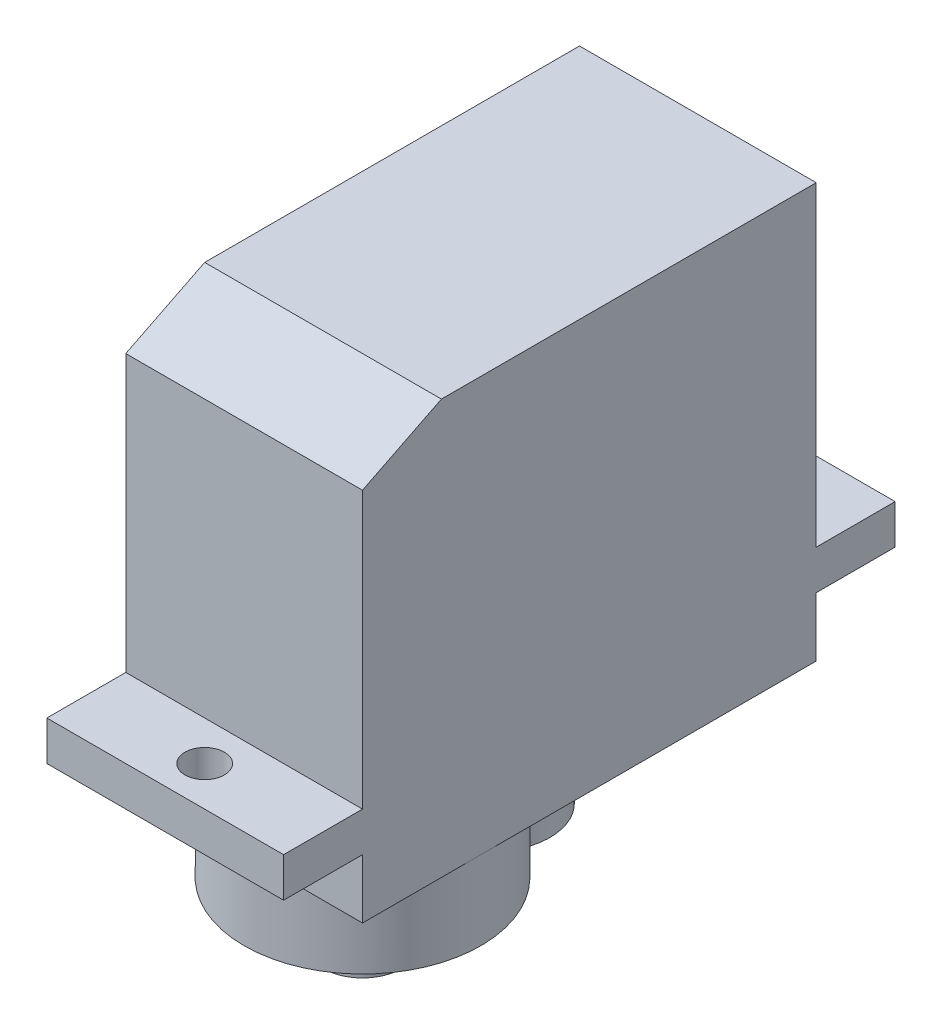
SolidWorks part; units mm, degrees
ref_plane "前视基准面" through (0, 0, 0) normal (0, 0, 1) x (1, 0, 0)
ref_plane "上视基准面" through (0, 0, 0) normal (0, 1, 0) x (1, 0, 0)
ref_plane "右视基准面" through (0, 0, 0) normal (1, 0, 0) x (0, 0, -1)
other "Configuration Table"
sketch "草图1" plane through (0, 0, 0) normal (0, 1, 0) x (1, 0, 0)
  line L1 (-6, 11.5) -> (6, 11.5)
  line L2 (-6, 11.5) -> (-6, -11.5)
  line L3 (-6, -11.5) -> (6, -11.5)
  line L4 (6, 11.5) -> (6, -11.5)
  line L5 (-6, 11.5) -> (6, -11.5) construction
  line L6 (-6, -11.5) -> (6, 11.5) construction
  point P0 (0, 0)
  dimension "D1" = 23
  dimension "D2" = 12
extrude "凸台-拉伸1" add sketch "草图1" along normal blind 21
ref_plane "基准面1" through (0, 5, 0) normal (0, -1, 0) x (-1, 0, 0)
sketch "草图2" plane through (0, 5, 0) normal (0, -1, 0) x (-1, 0, 0)
  line L0 (0, 13.35) -> (0, -14.1194) construction
  line L1 (-8.703, 0) -> (8.7957, 0) construction
  line L2 (-6, 11.5) -> (6, 11.5)
  line L3 (-6, 11.5) -> (-6, 15.5)
  line L4 (-6, 11.5) -> (-6, -11.5)
  line L5 (-6, -11.5) -> (6, -11.5)
  line L6 (6, -11.5) -> (6, 11.5)
  line L7 (6, 11.5) -> (-6, 11.5)
  line L8 (-6, 11.5) -> (-6, -11.5)
  line L9 (-6, -11.5) -> (6, -11.5)
  line L10 (6, -11.5) -> (6, 11.5)
  line L11 (6, 11.5) -> (-6, 11.5)
  line L12 (-6, 15.5) -> (6, 15.5)
  line L13 (6, 11.5) -> (6, 15.5)
  line L15 (-6, -11.5) -> (6, -11.5)
  line L16 (-6, -11.5) -> (-6, -15.5)
  line L17 (-6, -15.5) -> (6, -15.5)
  line L18 (6, -11.5) -> (6, -15.5)
  dimension "D2" = 12
  dimension "D3" = 4
  dimension "D4" = 6
  dimension "D5" = 4
  dimension "D1" = 0
extrude "凸台-拉伸2" add sketch "草图2" along normal blind 2 contours L18 L9 L16 L17 | L2 L13 L12 L3
sketch "草图3" plane through (0, 5, 0) normal (0, 1, 0) x (1, 0, 0)
  line L0 (0, -18.0752) -> (0, -9.3867) construction
  line L4 (-6, -11.5) -> (-6, -15.5)
  line L5 (-6, -15.5) -> (6, -15.5)
  line L6 (6, -15.5) -> (6, -11.5)
  line L7 (6, -11.5) -> (-6, -11.5)
  line L8 (-6, -11.5) -> (-6, -15.5)
  line L9 (-6, -15.5) -> (6, -15.5)
  line L10 (6, -15.5) -> (6, -11.5)
  line L11 (6, -11.5) -> (-6, -11.5)
  circle A0 centre (0, -13.5) radius 1
  dimension "D2" = 2
  dimension "D3" = 2
  dimension "D1" = 0
extrude "切除-拉伸2" cut sketch "草图3" against normal blind 2 contours A0
sketch "草图4" plane through (0, 5, 0) normal (0, 1, 0) x (1, 0, 0)
  line L0 (0, 17.7482) -> (0, 9.1792) construction
  line L4 (-6, 11.5) -> (6, 11.5)
  line L5 (6, 11.5) -> (6, 15.5)
  line L6 (6, 15.5) -> (-6, 15.5)
  line L7 (-6, 15.5) -> (-6, 11.5)
  line L8 (-6, 11.5) -> (6, 11.5)
  line L9 (6, 11.5) -> (6, 15.5)
  line L10 (6, 15.5) -> (-6, 15.5)
  line L11 (-6, 15.5) -> (-6, 11.5)
  circle A0 centre (0, 13.5) radius 1
  dimension "D2" = 2
  dimension "D3" = 2
  dimension "D1" = 0
extrude "切除-拉伸3" cut sketch "草图4" against normal blind 2 contours A0
sketch "草图5" plane through (0, 0, 0) normal (0, -1, 0) x (1, 0, 0)
  line L0 (0, 16.6208) -> (0, -17.5789) construction
  line L4 (6, -11.5) -> (6, 11.5)
  line L5 (6, 11.5) -> (-6, 11.5)
  line L6 (-6, 11.5) -> (-6, -11.5)
  line L7 (-6, -11.5) -> (6, -11.5)
  line L8 (6, -11.5) -> (6, 11.5)
  line L9 (6, 11.5) -> (-6, 11.5)
  line L10 (-6, 11.5) -> (-6, -11.5)
  line L11 (-6, -11.5) -> (6, -11.5)
  circle A0 centre (0, 5.5) radius 6
  circle A1 centre (0, -1) radius 3
  dimension "D2" = 12
  dimension "D3" = 6
  dimension "D4" = 6.5
  dimension "D1" = 0
extrude "凸台-拉伸3" add sketch "草图5" along normal blind 4 contours A0 L0 A1 | L0 A0 A1 | L0 A1 A0
sketch "草图6" plane through (0, -4, 0) normal (0, -1, 0) x (1, 0, 0)
  circle A0 centre (0, 5.5) radius 2
  arc A2 (2.7611, 0.1731) -> (-2.7611, 0.1731) centre (0, 5.5) ccw
  arc A3 (-2.7611, 0.1731) -> (2.7611, 0.1731) centre (0, -1) ccw
  arc A4 (2.7611, 0.1731) -> (-2.7611, 0.1731) centre (0, 5.5) ccw
  arc A5 (-2.7611, 0.1731) -> (2.7611, 0.1731) centre (0, -1) ccw
  dimension "D2" = 4
  dimension "D1" = 0
extrude "凸台-拉伸4" add sketch "草图6" along normal blind 3 contours A0
sketch "草图7" plane through (6, 0, 0) normal (1, 0, 0) x (0, 0, -1)
  line L0 (-11.5, 19) -> (-7.5, 21)
  line L1 (-11.5, 19) -> (-11.5, 21)
  line L2 (-11.5, 21) -> (-7.5, 21)
  line L13 (-11.5, 0) -> (-5.5, 0)
  line L14 (-5.5, 0) -> (11.5, 0)
  line L15 (11.5, 0) -> (11.5, 3)
  line L16 (11.5, 3) -> (15.5, 3)
  line L17 (15.5, 3) -> (15.5, 5)
  line L18 (15.5, 5) -> (11.5, 5)
  line L19 (11.5, 5) -> (11.5, 21)
  line L20 (11.5, 21) -> (-11.5, 21)
  line L21 (-11.5, 21) -> (-11.5, 5)
  line L22 (-11.5, 5) -> (-15.5, 5)
  line L23 (-15.5, 5) -> (-15.5, 3)
  line L24 (-15.5, 3) -> (-11.5, 3)
  line L25 (-11.5, 3) -> (-11.5, 0)
  line L26 (-11.5, 0) -> (-5.5, 0)
  line L27 (-5.5, 0) -> (11.5, 0)
  line L28 (11.5, 0) -> (11.5, 3)
  line L29 (11.5, 3) -> (15.5, 3)
  line L30 (15.5, 3) -> (15.5, 5)
  line L31 (15.5, 5) -> (11.5, 5)
  line L32 (11.5, 5) -> (11.5, 21)
  line L33 (11.5, 21) -> (-11.5, 21)
  line L34 (-11.5, 21) -> (-11.5, 5)
  line L35 (-11.5, 5) -> (-15.5, 5)
  line L36 (-15.5, 5) -> (-15.5, 3)
  line L37 (-15.5, 3) -> (-11.5, 3)
  line L38 (-11.5, 3) -> (-11.5, 0)
  line M24 (11.5, 21) -> (-11.5, 21)
  line M25 (-11.5, 21) -> (-11.5, 5)
  dimension "D2" = 2
  dimension "D3" = 4
  dimension "D1" = 0
extrude "切除-拉伸4" cut sketch "草图7" against normal through all contours L0 M25 M24
ref_plane "基准面17" through (0, -7, 0) normal (0, -1, 0) x (-1, 0, 0)
